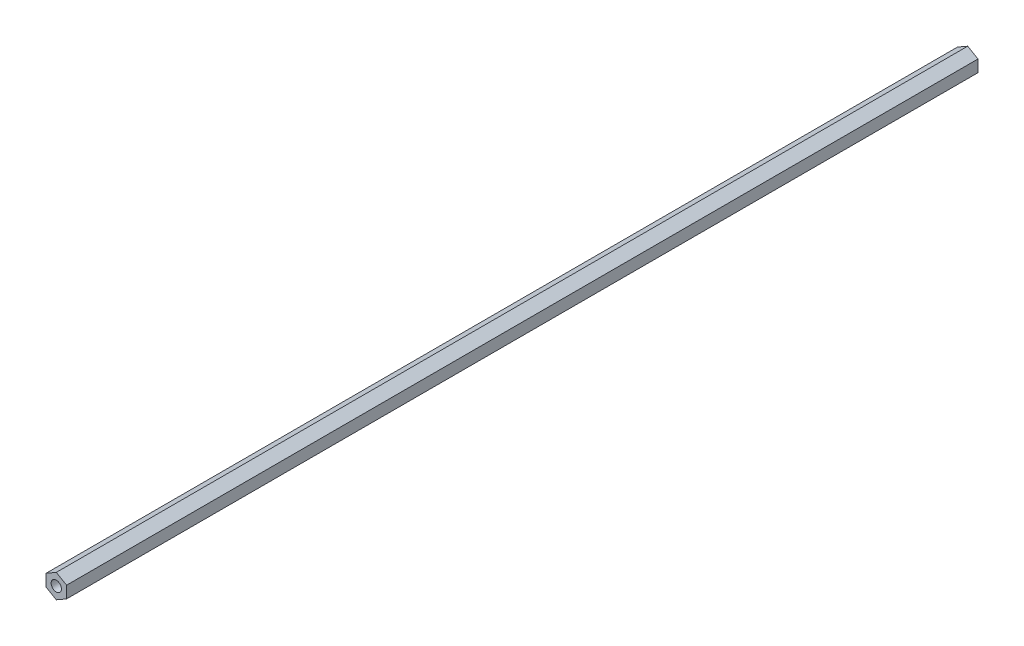
SolidWorks part; units mm, degrees
ref_plane "Front Plane" through (0, 0, 0) normal (0, 0, 1) x (1, 0, 0)
ref_plane "Top Plane" through (0, 0, 0) normal (0, 1, 0) x (1, 0, 0)
ref_plane "Right Plane" through (0, 0, 0) normal (1, 0, 0) x (0, 0, -1)
sketch "Sketch1" plane through (0, 0, 0) normal (0, 0, 1) x (1, 0, 0)
  line L1 (0, 7.3323) -> (-6.35, 3.6662) construction
  line L2 (-6.35, 3.6662) -> (-6.35, -3.6662) construction
  line L3 (-6.35, -3.6662) -> (0, -7.3323) construction
  line L4 (0, -7.3323) -> (6.35, -3.6662) construction
  line L5 (6.35, -3.6662) -> (6.35, 3.6662) construction
  line L6 (6.35, 3.6662) -> (0, 7.3323) construction
  circle A2 centre (0, 0) radius 6.35 construction
  dimension "Width" = 12.7
sketch "Sketch2" plane through (0, 0, 0) normal (1, 0, 0) x (0, 0, -1)
  line L0 (-280.9875, 7.3323) -> (280.9875, 7.3323) construction
  point P2 (0, 7.3323)
  point P3 (249.2375, 7.3323)
  point P4 (-249.2375, 7.3323)
  dimension "Length" = 561.975
  dimension "D2" = 31.75
  dimension "D1" = 31.75
sketch "Sketch3" plane through (0, 0, 0) normal (0, 0, 1) x (1, 0, 0)
  line L0 (-6.35, -3.6662) -> (0, -7.3323) construction
  line L1 (0, -7.3323) -> (6.35, -3.6662) construction
  line L2 (6.35, -3.6662) -> (6.35, 3.6662) construction
  line L3 (6.35, 3.6662) -> (0, 7.3323) construction
  line L4 (0, 7.3323) -> (-6.35, 3.6662) construction
  line L5 (-6.35, 3.6662) -> (-6.35, -3.6662) construction
  line L6 (-6.35, -3.6662) -> (0, -7.3323)
  line L7 (0, -7.3323) -> (6.35, -3.6662)
  line L8 (6.35, -3.6662) -> (6.35, 3.6662)
  line L9 (6.35, 3.6662) -> (0, 7.3323)
  line L10 (0, 7.3323) -> (-6.35, 3.6662)
  line L11 (-6.35, 3.6662) -> (-6.35, -3.6662)
extrude "Boss-Extrude2" add sketch "Sketch3" along normal up to vertex (280.9875 mm away) and the other way up to vertex (280.9875 mm away) up to point (0, 7.3323, 280.9875) other way up to point (0, 7.3323, -280.9875)
sketch "Sketch4" plane through (0, 0, 280.9875) normal (0, 0, 1) x (1, 0, 0)
  point P0 (0, 0)
hole_wizard "1/4 (0.25) Diameter Hole1" positions "Sketch5" profile "Sketch6" hole size "1/4" standard "ANSI Inch"
sketch "Sketch5" plane through (0, 0, 280.9875) normal (0, 0, 1) x (1, 0, 0)
  point P0 (0, 0)
sketch "Sketch6" plane through (0, 0, 280.9875) normal (1, 0, 0) x (0, -1, 0)
  line L0 (0, 0) -> (0, 27.3077)
  line L1 (0, 27.3077) -> (3.175, 25.4)
  line L2 (3.175, 25.4) -> (3.175, 0)
  line L5 (3.175, 0) -> (0, 0)
  line L10 (0, 27.3077) -> (-3.175, 25.4) construction
  line L11 (0, -6.35) -> (0, 107.95) construction
  dimension "Hole Dia." = 6.35
  dimension "Hole Depth" = 25.4
  dimension "Drill Angle" = 118
hole_wizard "1/4 (0.25) Diameter Hole2" positions "Sketch7" profile "Sketch8" hole size "1/4" standard "ANSI Inch"
sketch "Sketch7" plane through (0, 0, -280.9875) normal (0, 0, -1) x (-1, 0, 0)
  point P0 (0, 0)
sketch "Sketch8" plane through (0, 0, -280.9875) normal (1, 0, 0) x (0, 1, 0)
  line L0 (0, 0) -> (0, 27.3077)
  line L1 (0, 27.3077) -> (3.175, 25.4)
  line L2 (3.175, 25.4) -> (3.175, 0)
  line L5 (3.175, 0) -> (0, 0)
  line L10 (0, 27.3077) -> (-3.175, 25.4) construction
  line L11 (0, -6.35) -> (0, 107.95) construction
  dimension "Hole Dia." = 6.35
  dimension "Hole Depth" = 25.4
  dimension "Drill Angle" = 118
equation "\"D2@Sketch2\" = \"D1@Sketch2\""
equation "\"D1@Sketch2\" = \"Width@Sketch1\" * 2.5"
